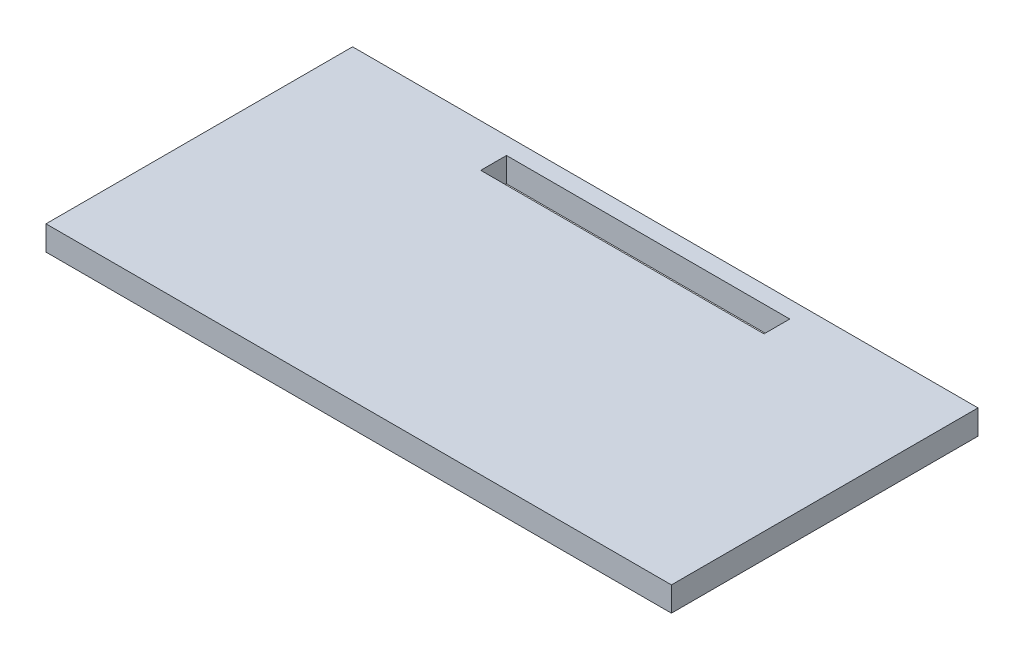
SolidWorks part; units mm, degrees
ref_plane "Front Plane" through (0, 0, 0) normal (0, 0, 1) x (1, 0, 0)
ref_plane "Top Plane" through (0, 0, 0) normal (0, 1, 0) x (1, 0, 0)
ref_plane "Right Plane" through (0, 0, 0) normal (1, 0, 0) x (0, 0, -1)
sketch "Sketch1" plane through (0, 0, 0) normal (0, 1, 0) x (1, 0, 0)
  line L1 (-29.2216, 12.3952) -> (21.7784, 12.3952)
  line L2 (-29.2216, 12.3952) -> (-29.2216, -12.6048)
  line L3 (-29.2216, -12.6048) -> (21.7784, -12.6048)
  line L4 (21.7784, 12.3952) -> (21.7784, -12.6048)
  dimension "D1" = 25
  dimension "D2" = 51
extrude "Boss-Extrude1" add sketch "Sketch1" along normal blind 2
sketch "Sketch3" plane through (0, 2, 0) normal (0, 1, 0) x (1, 0, 0)
  line L0 (21.7784, 12.3952) -> (-29.2216, 12.3952) construction
  line L1 (-10.2716, 10.9952) -> (2.8284, 10.9952)
  line L2 (-10.2716, 10.9952) -> (-10.2716, 8.8952)
  line L3 (-10.2716, 8.8952) -> (2.8284, 8.8952)
  line L4 (2.8284, 10.9952) -> (2.8284, 8.8952)
  line L5 (21.7784, -12.6048) -> (21.7784, 12.3952) construction
  line L6 (-29.2216, 12.3952) -> (-29.2216, -12.6048) construction
  dimension "D1" = 1.4
  dimension "D2" = 18.95
  dimension "D3" = 18.95
  dimension "D4" = 2.1
extrude "Cut-Extrude1" cut sketch "Sketch3" against normal through all both and the other way through all
sketch "Sketch4" plane through (0, 2, 0) normal (0, 1, 0) x (1, 0, 0)
  line L0 (2.8284, 10.9952) -> (-10.2716, 10.9952) construction
  line L1 (-15.2716, 10.9952) -> (7.8284, 10.9952)
  line L2 (-15.2716, 10.9952) -> (-15.2716, 8.8952)
  line L3 (-15.2716, 8.8952) -> (7.8284, 8.8952)
  line L4 (7.8284, 10.9952) -> (7.8284, 8.8952)
  line L5 (-10.2716, 8.8952) -> (2.8284, 8.8952) construction
  line L6 (-3.7216, 12.3952) -> (-3.7216, -4.1845) construction
  line L7 (21.7784, 12.3952) -> (-29.2216, 12.3952) construction
  dimension "D1" = 0
  dimension "D2" = 0
  dimension "D3" = 11.55
  dimension "D4" = 11.55
extrude "Cut-Extrude2" cut sketch "Sketch4" against normal blind 10
